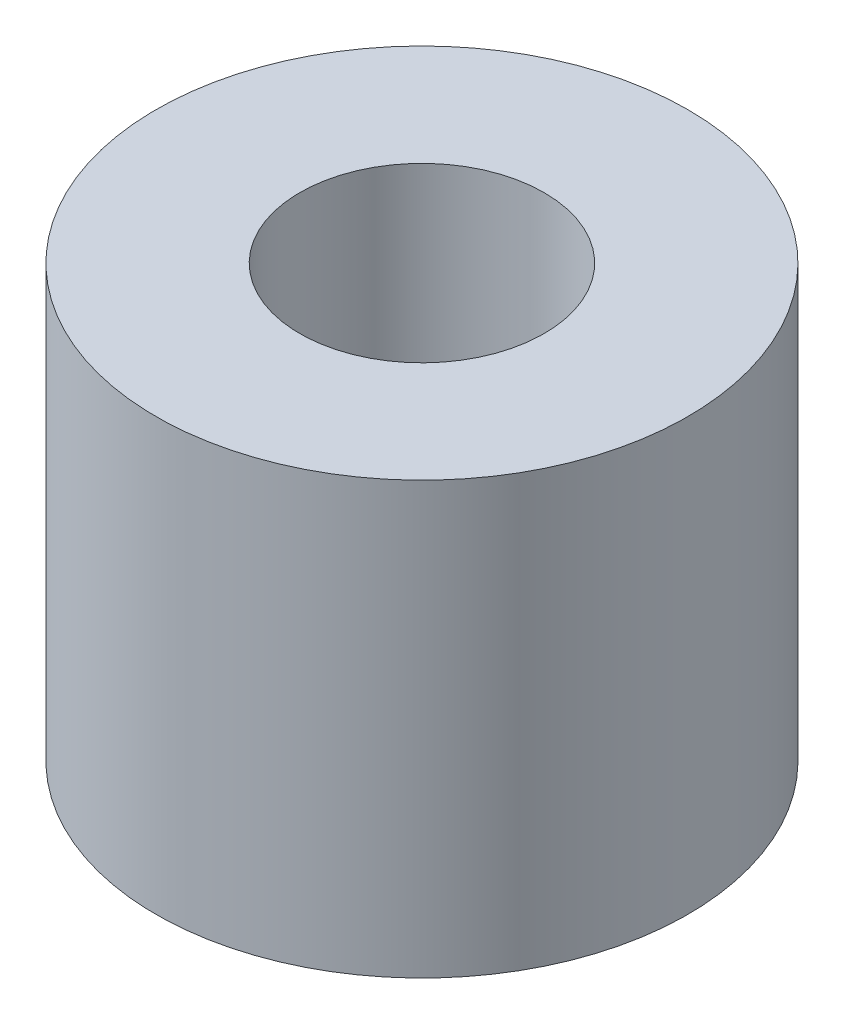
SolidWorks part; units mm, degrees
material "AISI 304"
ref_plane "Alzado" through (0, 0, 0) normal (0, 0, 1) x (1, 0, 0)
ref_plane "Planta" through (0, 0, 0) normal (0, 1, 0) x (1, 0, 0)
ref_plane "Vista lateral" through (0, 0, 0) normal (1, 0, 0) x (0, 0, -1)
sketch "Sketch1" plane through (0, 0, 0) normal (0, 0, 1) x (1, 0, 0)
  line L0 (1.7, -3) -> (3.7, -3)
  line L1 (3.7, -3) -> (3.7, 3)
  line L2 (3.7, 3) -> (1.7, 3)
  line L3 (1.7, 3) -> (1.7, -3)
  line L4 (0, -7) -> (0, 7) construction
revolve "Ojal_guia" add sketch "Sketch1" angle 360 about L4
